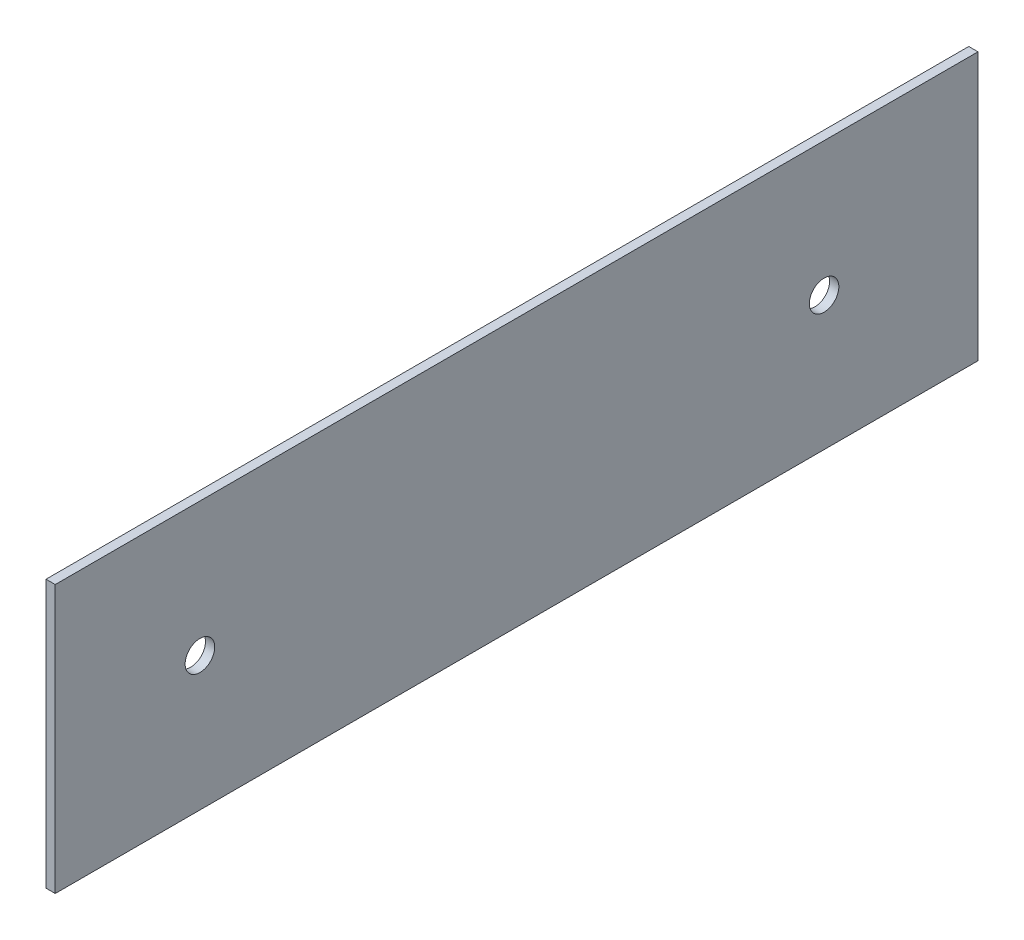
SolidWorks part; units mm, degrees
material "2024-T361"
ref_plane "Front Plane" through (0, 0, 0) normal (0, 0, 1) x (1, 0, 0)
ref_plane "Top Plane" through (0, 0, 0) normal (0, 1, 0) x (1, 0, 0)
ref_plane "Right Plane" through (0, 0, 0) normal (1, 0, 0) x (0, 0, -1)
sketch "Sketch2" plane through (0, 0, 0) normal (1, 0, 0) x (0, 0, -1)
  line L0 (0, 46.8015) -> (0, -186.831) construction
  line L1 (-250, 85) -> (250, 85)
  line L2 (-250, 85) -> (-250, -60)
  line L3 (-250, -60) -> (250, -60)
  line L4 (250, 85) -> (250, -60)
  line L5 (71.2891, 0) -> (-114.3104, 0) construction
  line L6 (250, -60) -> (-250, -60) construction
  line L7 (250, -60) -> (-250, -60) construction
  dimension "D1" = 500
  dimension "D2" = 145
extrude "Boss-Extrude1" add sketch "Sketch2" along normal blind 5
sketch "Sketch3" plane through (0, 0, 0) normal (-1, 0, 0) x (0, 0, 1)
  line L0 (250, 12.5) -> (93.201, 12.5) construction
  line L1 (250, 85) -> (250, -60) construction
  line L2 (93.201, 12.5) -> (171.6005, 12.5) construction
  line L3 (171.6005, 12.5) -> (171.6005, 85) construction
  line L4 (-250, 85) -> (250, 85) construction
  line L5 (171.6005, 12.5) -> (171.6005, -60) construction
  line L6 (250, -60) -> (-250, -60) construction
  circle A0 centre (171.6005, 12.5) radius 125 construction
  circle A1 centre (171.6005, 12.5) radius 8
  dimension "D1" = 250
  dimension "D2" = 16
extrude "Cut-Extrude1" cut sketch "Sketch3" against normal up to next
ref_plane "Plane1" through (0, 0, 2.5) normal (0, 0, 1) x (1, 0, 0)
mirror "Mirror1" about plane through (0, 0, 2.5) normal (0, 0, 1) of "Cut-Extrude1"
